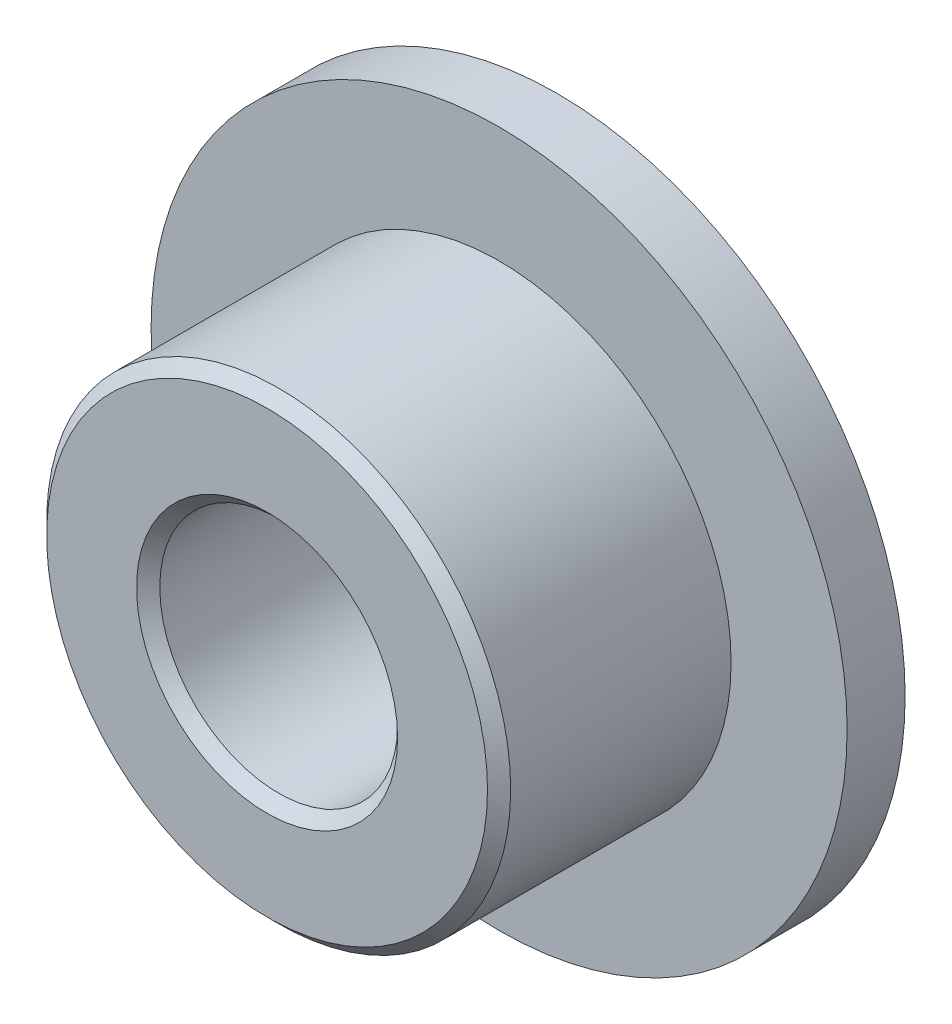
SolidWorks part; units mm, degrees
ref_plane "前视基准面" through (0, 0, 0) normal (0, 0, 1) x (1, 0, 0)
ref_plane "上视基准面" through (0, 0, 0) normal (0, 1, 0) x (1, 0, 0)
ref_plane "右视基准面" through (0, 0, 0) normal (1, 0, 0) x (0, 0, -1)
sketch "草图1" plane through (0, 0, 0) normal (0, 0, 1) x (1, 0, 0)
  circle A0 centre (0, 0) radius 6
  dimension "D1" = 12
extrude "凸台-拉伸1" add sketch "草图1" along normal blind 1
sketch "草图2" plane through (0, 0, 1) normal (0, 0, 1) x (1, 0, 0)
  circle A0 centre (0, 0) radius 4
  dimension "D1" = 8
extrude "凸台-拉伸2" add sketch "草图2" along normal blind 4
sketch "草图3" plane through (0, 0, 5) normal (0, 0, 1) x (1, 0, 0)
  circle A0 centre (0, 0) radius 2.05
  dimension "D1" = 4.1
extrude "切除-拉伸1" cut sketch "草图3" against normal through all
chamfer "倒角1" distance 0.2 angle 45 3 edges at (2.05, 0, 0) (2.05, 0, 5) (4, 0, 5)
